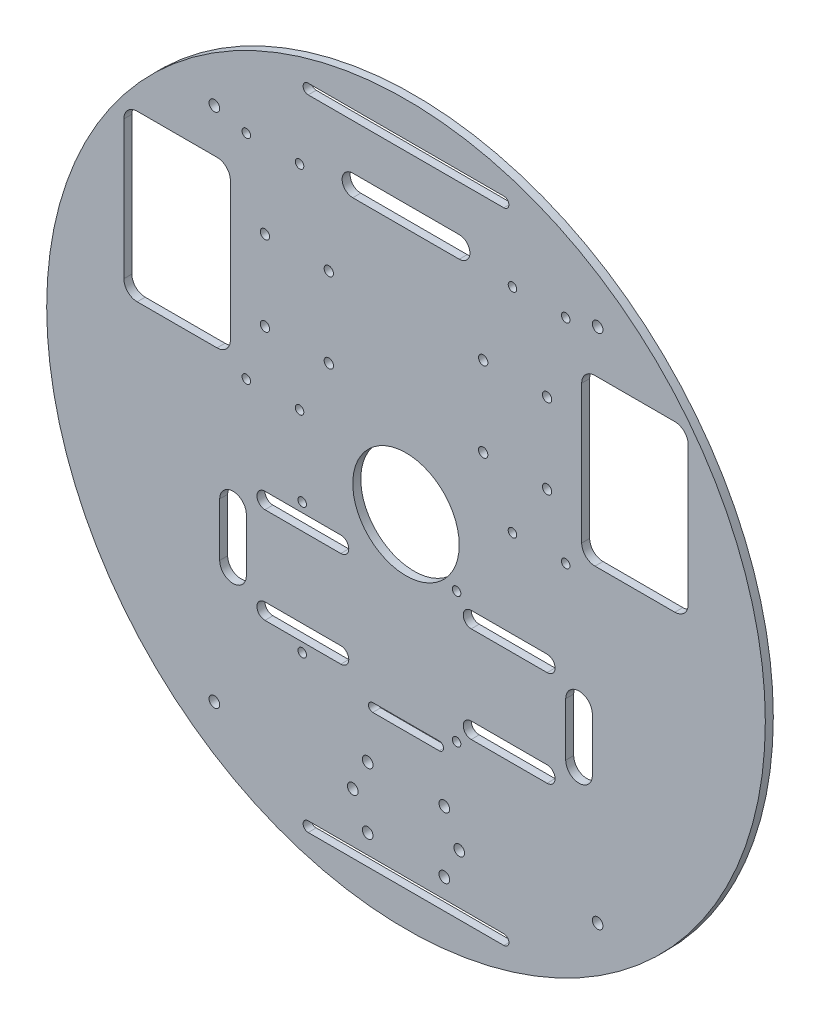
SolidWorks part; units mm, degrees
ref_plane "前视基准面" through (0, 0, 0) normal (0, 0, 1) x (1, 0, 0)
ref_plane "上视基准面" through (0, 0, 0) normal (0, 1, 0) x (1, 0, 0)
ref_plane "右视基准面" through (0, 0, 0) normal (1, 0, 0) x (0, 0, -1)
sketch "草图1" plane through (0, 0, 0) normal (0, 0, 1) x (1, 0, 0)
  line L0 (0, 135) -> (0, -135) construction
  line L1 (0, -99.3042) -> (86, 49.6521) construction
  line L2 (86, 49.6521) -> (-86, 49.6521) construction
  line L3 (-86, 49.6521) -> (0, -99.3042) construction
  line L4 (-106, 80.6521) -> (-66, 80.6521)
  line L5 (-106, 80.6521) -> (-106, 18.6521)
  line L6 (-106, 18.6521) -> (-66, 18.6521)
  line L7 (-66, 80.6521) -> (-66, 18.6521)
  line L8 (-106, 80.6521) -> (-66, 18.6521) construction
  line L9 (-106, 18.6521) -> (-66, 80.6521) construction
  line L10 (106, 80.6521) -> (66, 80.6521)
  line L11 (66, 80.6521) -> (66, 18.6521)
  line L12 (106, 80.6521) -> (66, 18.6521) construction
  line L13 (106, 18.6521) -> (66, 18.6521)
  line L14 (106, 18.6521) -> (66, 80.6521) construction
  line L15 (106, 80.6521) -> (106, 18.6521)
  line L17 (-14.4, -87.8042) -> (14.4, -87.8042) construction
  line L18 (-14.4, -87.8042) -> (-14.4, -110.8042) construction
  line L19 (-14.4, -110.8042) -> (14.4, -110.8042) construction
  line L20 (14.4, -87.8042) -> (14.4, -110.8042) construction
  line L21 (-14.4, -87.8042) -> (14.4, -110.8042) construction
  line L22 (-14.4, -110.8042) -> (14.4, -87.8042) construction
  line L29 (-53, 64.6521) -> (-29, 64.6521) construction
  line L30 (-53, 64.6521) -> (-53, 34.6521) construction
  line L31 (-53, 34.6521) -> (-29, 34.6521) construction
  line L32 (-29, 64.6521) -> (-29, 34.6521) construction
  line L33 (-53, 64.6521) -> (-29, 34.6521) construction
  line L34 (-53, 34.6521) -> (-29, 64.6521) construction
  circle A0 centre (0, 0) radius 135
  circle A1 centre (0, 0) radius 49.6521 construction
  circle A2 centre (-53, 64.6521) radius 1.75
  circle A3 centre (-29, 64.6521) radius 1.75
  circle A4 centre (-53, 34.6521) radius 1.75
  circle A5 centre (-29, 34.6521) radius 1.75
  circle A6 centre (53, 34.6521) radius 1.75
  circle A7 centre (29, 34.6521) radius 1.75
  circle A8 centre (29, 64.6521) radius 1.75
  circle A9 centre (53, 64.6521) radius 1.75
  circle A10 centre (20, -99.3042) radius 2
  circle A11 centre (14.4, -87.8042) radius 2
  circle A12 centre (14.4, -110.8042) radius 2
  circle A13 centre (-14.4, -87.8042) radius 2
  circle A14 centre (-14.4, -110.8042) radius 2
  circle A15 centre (-20, -99.3042) radius 2
  point P25 (0, 49.6521)
  point P26 (-41, 49.6521)
  point P30 (0, 49.6521)
  dimension "D1" = 270
  dimension "D9" = 3.5
  dimension "D10" = 3.5
  dimension "D11" = 3.5
  dimension "D12" = 3.5
  dimension "D14" = 20
  dimension "D2" = 40
  dimension "D3" = 62
  dimension "D4" = 41
  dimension "D5" = 25
  dimension "D6" = 28.8
  dimension "D7" = 24
  dimension "D8" = 30
  dimension "D13" = 23
extrude "凸台-拉伸1" add sketch "草图1" along normal blind 3
fillet "圆角1" radius 5 8 edges at (106, 80.6521, 1.5) (66, 80.6521, 1.5) (66, 18.6521, 1.5) (106, 18.6521, 1.5) (-66, 18.6521, 1.5) (-106, 18.6521, 1.5) (-106, 80.6521, 1.5) (-66, 80.6521, 1.5)
sketch "草图2" plane through (0, 0, 3) normal (0, 0, 1) x (1, 0, 0)
  line L1 (-72, 97) -> (72, 97) construction
  line L2 (-72, 97) -> (-72, -97) construction
  line L3 (-72, -97) -> (72, -97) construction
  line L4 (72, 97) -> (72, -97) construction
  line L5 (-72, 97) -> (72, -97) construction
  line L6 (-72, -97) -> (72, 97) construction
  line L7 (24.5056, -55) -> (53, -55)
  line L8 (-53, -19) -> (-24.5056, -19)
  line L9 (-53, -19) -> (-53, -61) construction
  line L10 (-53, -61) -> (-24.5056, -61)
  line L11 (53, -19) -> (53, -61) construction
  line L12 (-53, -19) -> (53, -61) construction
  line L13 (-53, -61) -> (53, -19) construction
  line L14 (-53, -25) -> (-24.5056, -25)
  line L15 (-53, -25) -> (-53, -55) construction
  line L16 (-53, -55) -> (-24.5056, -55)
  line L17 (53, -25) -> (53, -55) construction
  line L18 (-53, -25) -> (53, -55) construction
  line L19 (-53, -55) -> (53, -25) construction
  line L20 (24.5056, -25) -> (53, -25)
  line L21 (24.5056, -19) -> (53, -19)
  line L22 (24.5056, -61) -> (53, -61)
  line L23 (40, 94) -> (40, 14) construction
  line L24 (-65, -30) -> (65, -30) construction
  line L25 (-65, -30) -> (-65, -50) construction
  line L26 (-65, -50) -> (65, -50) construction
  line L27 (65, -30) -> (65, -50) construction
  line L28 (-65, -30) -> (65, -50) construction
  line L29 (-65, -50) -> (65, -30) construction
  line L30 (-70, -30) -> (-60, -30) construction
  line L31 (-70, -30) -> (-70, -50)
  line L32 (-70, -50) -> (-60, -50) construction
  line L33 (-60, -30) -> (-60, -50)
  line L34 (-70, -30) -> (-60, -50) construction
  line L35 (-70, -50) -> (-60, -30) construction
  line L36 (60, -30) -> (70, -30) construction
  line L37 (60, -30) -> (60, -50)
  line L38 (60, -50) -> (70, -50) construction
  line L39 (70, -30) -> (70, -50)
  line L40 (60, -30) -> (70, -50) construction
  line L41 (60, -50) -> (70, -30) construction
  line L43 (35, -12.5) -> (-35, -12.5) construction
  line L44 (35, -12.5) -> (35, -67.5) construction
  line L45 (-42.5, -12) -> (42.5, -12) construction
  line L46 (-42.5, -12) -> (-42.5, -68) construction
  line L47 (-42.5, -68) -> (42.5, -68) construction
  line L48 (-135, 0) -> (135, 0) construction
  line L49 (-36.7556, -118.1) -> (36.7556, -121.9) construction
  line L50 (-36.7556, 121.9) -> (36.7556, 121.9)
  line L51 (-36.7556, 121.9) -> (-36.7556, 118.1) construction
  line L52 (-36.7556, 118.1) -> (36.7556, 118.1)
  line L53 (36.7556, 121.9) -> (36.7556, 118.1) construction
  line L54 (-36.7556, 121.9) -> (36.7556, 118.1) construction
  line L55 (-36.7556, 118.1) -> (36.7556, 121.9) construction
  line L56 (-36.7556, -121.9) -> (36.7556, -118.1) construction
  line L57 (36.7556, -121.9) -> (36.7556, -118.1) construction
  line L58 (-36.7556, -121.9) -> (-36.7556, -118.1) construction
  line L59 (-36.7556, -118.1) -> (36.7556, -118.1)
  line L60 (-36.7556, -121.9) -> (36.7556, -121.9)
  line L61 (-40, 94) -> (-40, 14) construction
  line L62 (-60, 94) -> (60, 94) construction
  line L63 (-60, 94) -> (-60, 14) construction
  line L64 (-60, 14) -> (60, 14) construction
  line L65 (60, 94) -> (60, 14) construction
  line L66 (-60, 94) -> (60, 14) construction
  line L67 (-60, 14) -> (60, 94) construction
  line L68 (42.5, -12) -> (42.5, -68) construction
  line L69 (-42.5, -12) -> (42.5, -68) construction
  line L70 (-42.5, -68) -> (42.5, -12) construction
  line L71 (-39, -15.5) -> (19, -15.5) construction
  line L72 (-39, -15.5) -> (-39, -64.5) construction
  line L73 (-39, -64.5) -> (19, -64.5) construction
  line L74 (19, -15.5) -> (19, -64.5) construction
  line L75 (-39, -15.5) -> (19, -64.5) construction
  line L76 (-39, -64.5) -> (19, -15.5) construction
  line L77 (35, -67.5) -> (-35, -67.5) construction
  line L78 (-35, -12.5) -> (-35, -67.5) construction
  line L79 (35, -12.5) -> (-35, -67.5) construction
  line L80 (35, -67.5) -> (-35, -12.5) construction
  line L81 (12.5, -70.7) -> (-12.5, -70.7)
  line L82 (12.5, -70.7) -> (12.5, -67.5) construction
  line L83 (12.5, -67.5) -> (-12.5, -67.5)
  line L84 (-12.5, -70.7) -> (-12.5, -67.5) construction
  line L85 (12.5, -70.7) -> (-12.5, -67.5) construction
  line L86 (12.5, -67.5) -> (-12.5, -70.7) construction
  line L87 (20, 101) -> (-20, 101)
  line L88 (20, 101) -> (20, 93) construction
  line L89 (20, 93) -> (-20, 93)
  line L90 (-20, 101) -> (-20, 93) construction
  line L91 (20, 101) -> (-20, 93) construction
  line L92 (20, 93) -> (-20, 101) construction
  circle A0 centre (0, 0) radius 20
  circle A1 centre (-72, 97) radius 2
  circle A2 centre (72, 97) radius 2
  circle A3 centre (72, -97) radius 2
  circle A4 centre (-72, -97) radius 2
  arc A5 (-53, -19) -> (-53, -25) centre (-53, -22) ccw
  arc A6 (-53, -55) -> (-53, -61) centre (-53, -58) ccw
  arc A7 (-24.5056, -19) -> (-24.5056, -25) centre (-24.5056, -22) cw
  arc A8 (-24.5056, -61) -> (-24.5056, -55) centre (-24.5056, -58) ccw
  arc A9 (53, -55) -> (53, -61) centre (53, -58) cw
  arc A10 (53, -19) -> (53, -25) centre (53, -22) cw
  arc A11 (24.5056, -61) -> (24.5056, -55) centre (24.5056, -58) cw
  arc A12 (24.5056, -19) -> (24.5056, -25) centre (24.5056, -22) ccw
  arc A13 (-70, -30) -> (-60, -30) centre (-65, -30) cw
  arc A14 (-70, -50) -> (-60, -50) centre (-65, -50) ccw
  arc A15 (60, -30) -> (70, -30) centre (65, -30) cw
  arc A16 (60, -50) -> (70, -50) centre (65, -50) ccw
  circle A17 centre (-60, 94) radius 1.6
  circle A18 centre (-60, 14) radius 1.6
  circle A19 centre (-40, 94) radius 1.6
  circle A20 centre (-40, 14) radius 1.6
  circle A21 centre (60, 14) radius 1.6
  circle A22 centre (60, 94) radius 1.6
  circle A23 centre (40, 94) radius 1.6
  circle A24 centre (40, 14) radius 1.6
  circle A25 centre (0, 0) radius 135 construction
  arc A26 (36.7556, 121.9) -> (36.7556, 118.1) centre (36.7556, 120) cw
  arc A27 (-36.7556, 121.9) -> (-36.7556, 118.1) centre (-36.7556, 120) ccw
  arc A28 (-36.7556, -121.9) -> (-36.7556, -118.1) centre (-36.7556, -120) cw
  arc A29 (36.7556, -121.9) -> (36.7556, -118.1) centre (36.7556, -120) ccw
  circle A30 centre (-39, -15.5) radius 1.6
  circle A31 centre (19, -15.5) radius 1.6
  circle A32 centre (-39, -64.5) radius 1.6
  circle A33 centre (19, -64.5) radius 1.6
  arc A34 (-12.5, -67.5) -> (-12.5, -70.7) centre (-12.5, -69.1) ccw
  arc A35 (12.5, -67.5) -> (12.5, -70.7) centre (12.5, -69.1) cw
  arc A36 (20, 101) -> (20, 93) centre (20, 97) cw
  arc A37 (-20, 101) -> (-20, 93) centre (-20, 97) ccw
  point P25 (0, 54)
  point P32 (0, -40)
  point P37 (-65, -40)
  point P38 (0, -40)
  point P39 (0, -40)
  point P52 (65, -40)
  point P61 (0, -40)
  point P77 (-10, -40)
  point P83 (0, 120)
  point P96 (0, -120)
  point P97 (0, -40)
  point P106 (-42.5, -40)
  point P111 (0, -40)
  point P116 (0, -69.1)
  dimension "D1" = 144
  dimension "D13" = 3.8
  dimension "D15" = 4
  dimension "D16" = 4
  dimension "D17" = 4
  dimension "D18" = 4
  dimension "D12" = 56
  dimension "D26" = 6
  dimension "D27" = 3
  dimension "D28" = 3
  dimension "D2" = 194
  dimension "D3" = 30
  dimension "D4" = 20
  dimension "D5" = 106
  dimension "D6" = 130
  dimension "D7" = 40
  dimension "D8" = 10
  dimension "D9" = 10
  dimension "D10" = 54
  dimension "D14" = 120
  dimension "D19" = 80
  dimension "D20" = 120
  dimension "D21" = 85
  dimension "D22" = 3.5
  dimension "D23" = 58
  dimension "D24" = 49
  dimension "D25" = 3.5
  dimension "D29" = 70
  dimension "D30" = 55
  dimension "D31" = 25
  dimension "D32" = 3.2
  dimension "D33" = 8
  dimension "D34" = 40
extrude "切除-拉伸1" cut sketch "草图2" against normal blind 10
sketch "草图3" plane through (0, 0, 3) normal (0, 0, 1) x (1, 0, 0)
  line L0 (0, 0) -> (0, -135) construction
  line L1 (0, 93) -> (0, 0) construction
  line L2 (35, -8.8786) -> (-35, -8.8786) construction
  line L3 (35, -8.8786) -> (35, -63.8786) construction
  line L4 (35, -63.8786) -> (-35, -63.8786) construction
  line L5 (-35, -8.8786) -> (-35, -63.8786) construction
  line L6 (35, -8.8786) -> (-35, -63.8786) construction
  line L7 (35, -63.8786) -> (-35, -8.8786) construction
  line L8 (-20, 93) -> (20, 93) construction
  circle A0 centre (0, 0) radius 135 construction
  point P6 (0, -36.3786)
  dimension "D1" = 55
  dimension "D2" = 70
  dimension "D3" = 93
